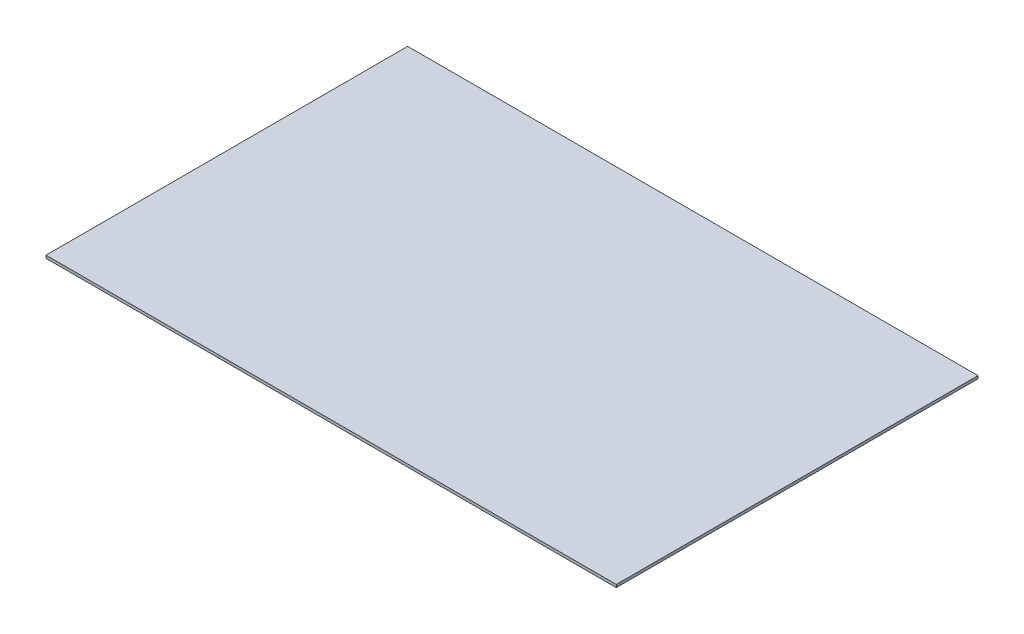
SolidWorks part; units mm, degrees
material "Mahogany"
ref_plane "Front Plane" through (0, 0, 0) normal (0, 0, 1) x (1, 0, 0)
ref_plane "Top Plane" through (0, 0, 0) normal (0, 1, 0) x (1, 0, 0)
ref_plane "Right Plane" through (0, 0, 0) normal (1, 0, 0) x (0, 0, -1)
sketch "Sketch1" plane through (0, 0, 0) normal (0, 1, 0) x (1, 0, 0)
  line L1 (-257, -163) -> (257, -163)
  line L2 (-257, -163) -> (-257, 163)
  line L3 (-257, 163) -> (257, 163)
  line L4 (257, -163) -> (257, 163)
  line L5 (-257, -163) -> (257, 163) construction
  line L6 (-257, 163) -> (257, -163) construction
  point P0 (0, 0)
  dimension "D1" = 514
  dimension "D2" = 326
extrude "Boss-Extrude1" add sketch "Sketch1" along normal mid plane 2.5
